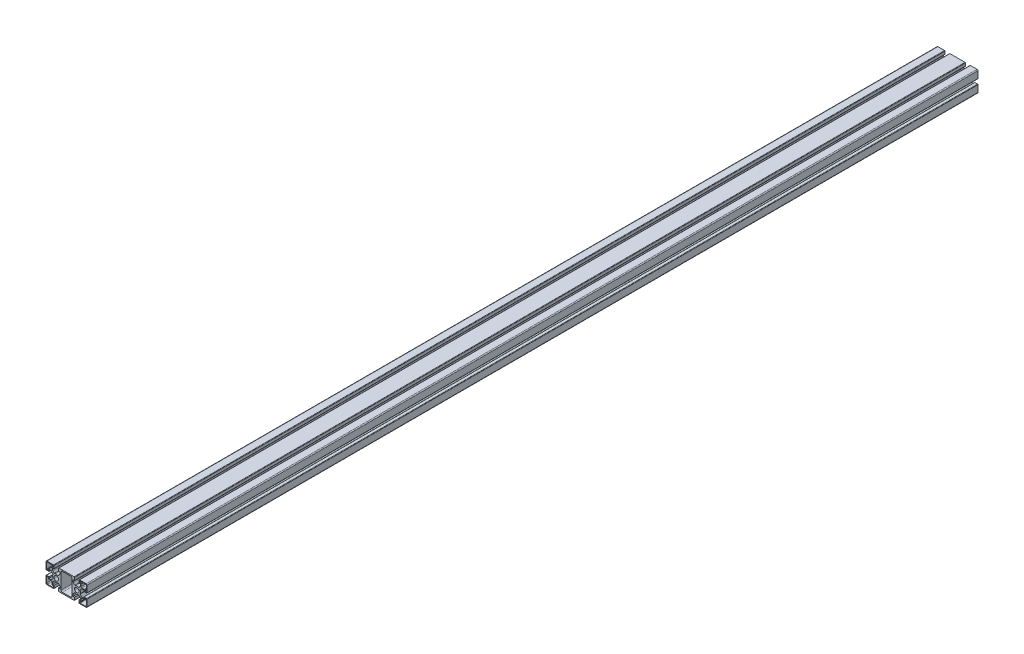
SolidWorks part; units mm, degrees
ref_plane "Front Plane" through (0, 0, 0) normal (0, 0, 1) x (1, 0, 0)
ref_plane "Top Plane" through (0, 0, 0) normal (0, 1, 0) x (1, 0, 0)
ref_plane "Right Plane" through (0, 0, 0) normal (1, 0, 0) x (0, 0, -1)
sketch "Sketch1" plane through (0, 0, 0) normal (0, 0, 1) x (1, 0, 0)
  line L0 (-5, -15.7059) -> (-8, -15.7059)
  line L1 (-20.5, -22.5) -> (-6, -22.5)
  line L2 (-22.5, -20.5) -> (-22.5, -6)
  line L5 (-21.9142, -21.9142) -> (22.5, 22.5) construction
  line L6 (-22.5, 22.5) -> (22.5, -22.5) construction
  line L7 (-20.5, -22.5) -> (-6, -22.5)
  line L8 (-22.5, -20.5) -> (-22.5, -6)
  line L10 (-5, -21.5) -> (-5, -15.7059)
  line L11 (-8, -15.7059) -> (-8, -11.9485)
  line L12 (-7.1213, -9.8272) -> (-4.6684, -7.3742)
  line L14 (-19, -21) -> (-7.5, -21)
  line L15 (-6.5, -20) -> (-6.5, -18.2059)
  line L16 (-7.5, -17.2059) -> (-8.5, -17.2059)
  line L17 (-9.5, -16.2059) -> (-9.5, -11.5)
  line L18 (-16.2059, -9.5) -> (-11.5, -9.5)
  line L19 (-17.2059, -7.5) -> (-17.2059, -8.5)
  line L20 (-20, -6.5) -> (-18.2059, -6.5)
  line L21 (-21, -19) -> (-21, -7.5)
  line L22 (-9.8272, -7.1213) -> (-7.3742, -4.6684)
  line L23 (-15.7059, -8) -> (-11.9485, -8)
  line L24 (-15.7059, -5) -> (-15.7059, -8)
  line L25 (-21.5, -5) -> (-15.7059, -5)
  line L26 (0, 27.7778) -> (0, -29.5537) construction
  line L28 (-9.5, 16.2059) -> (-9.5, 11.5)
  line L29 (-16.2059, 9.5) -> (-11.5, 9.5)
  line L30 (-17.2059, 7.5) -> (-17.2059, 8.5)
  line L31 (-20, 6.5) -> (-18.2059, 6.5)
  line L32 (-21, 19) -> (-21, 7.5)
  line L33 (-19, 21) -> (-7.5, 21)
  line L34 (-6.5, 20) -> (-6.5, 18.2059)
  line L35 (-7.5, 17.2059) -> (-8.5, 17.2059)
  line L36 (-22.5, 20.5) -> (-22.5, 6)
  line L37 (-20.5, 22.5) -> (-6, 22.5)
  line L38 (-5, 21.5) -> (-5, 15.7059)
  line L39 (-5, 15.7059) -> (-8, 15.7059)
  line L40 (-8, 15.7059) -> (-8, 11.9485)
  line L41 (-7.1213, 9.8272) -> (-4.6684, 7.3742)
  line L42 (-9.8272, 7.1213) -> (-7.3742, 4.6684)
  line L43 (-15.7059, 8) -> (-11.9485, 8)
  line L44 (-15.7059, 5) -> (-15.7059, 8)
  line L45 (-21.5, 5) -> (-15.7059, 5)
  line L54 (6, 22.5) -> (39, 22.5)
  line L56 (0, 0) -> (22.5, 0) construction
  line L57 (6, -22.5) -> (39, -22.5)
  line L58 (10.5, 17) -> (10.5, -17)
  line L59 (13.5, -20) -> (31.5, -20)
  line L60 (7.1213, 9.8272) -> (4.6684, 7.3742)
  line L61 (8, 15.7059) -> (8, 11.9485)
  line L62 (5, 15.7059) -> (8, 15.7059)
  line L63 (5, 21.5) -> (5, 15.7059)
  line L72 (13.5, 20) -> (31.5, 20)
  line L73 (22.5, 22.5) -> (22.5, -22.5) construction
  line L74 (5, -21.5) -> (5, -15.7059)
  line L75 (5, -15.7059) -> (8, -15.7059)
  line L76 (8, -15.7059) -> (8, -11.9485)
  line L77 (7.1213, -9.8272) -> (4.6684, -7.3742)
  line L78 (37.8787, -9.8272) -> (40.3316, -7.3742)
  line L79 (37, -15.7059) -> (37, -11.9485)
  line L80 (40, -15.7059) -> (37, -15.7059)
  line L81 (40, -21.5) -> (40, -15.7059)
  line L82 (21.5, 5) -> (15.7059, 5) [skipped]
  line L83 (20, 6.5) -> (18.2059, 6.5) [skipped]
  line L84 (21, 19) -> (21, 7.5) [skipped]
  line L85 (22.5, 20.5) -> (22.5, 6) [skipped]
  line L86 (15.7059, 5) -> (15.7059, 8) [skipped]
  line L87 (15.7059, 8) -> (11.9485, 8) [skipped]
  line L88 (16.2059, 9.5) -> (11.5, 9.5) [skipped]
  line L89 (17.2059, 7.5) -> (17.2059, 8.5) [skipped]
  line L90 (9.5, 16.2059) -> (9.5, 11.5) [skipped]
  line L91 (7.5, 17.2059) -> (8.5, 17.2059) [skipped]
  line L92 (6.5, 20) -> (6.5, 18.2059) [skipped]
  line L93 (19, 21) -> (7.5, 21) [skipped]
  line L94 (9.8272, 7.1213) -> (7.3742, 4.6684) [skipped]
  line L95 (6.5, -20) -> (6.5, -18.2059) [skipped]
  line L96 (19, -21) -> (7.5, -21) [skipped]
  line L97 (7.5, -17.2059) -> (8.5, -17.2059) [skipped]
  line L98 (9.5, -16.2059) -> (9.5, -11.5) [skipped]
  line L99 (22.5, -20.5) -> (22.5, -6) [skipped]
  line L100 (21, -19) -> (21, -7.5) [skipped]
  line L101 (20, -6.5) -> (18.2059, -6.5) [skipped]
  line L102 (21.5, -5) -> (15.7059, -5) [skipped]
  line L103 (17.2059, -7.5) -> (17.2059, -8.5) [skipped]
  line L104 (15.7059, -5) -> (15.7059, -8) [skipped]
  line L105 (9.8272, -7.1213) -> (7.3742, -4.6684) [skipped]
  line L106 (15.7059, -8) -> (11.9485, -8) [skipped]
  line L107 (16.2059, -9.5) -> (11.5, -9.5) [skipped]
  line L108 (20.5, 22.5) -> (6, 22.5) [skipped]
  line L109 (20.5, -22.5) -> (6, -22.5) [skipped]
  line L110 (40, 21.5) -> (40, 15.7059)
  line L111 (40, 15.7059) -> (37, 15.7059)
  line L112 (37, 15.7059) -> (37, 11.9485)
  line L113 (37.8787, 9.8272) -> (40.3316, 7.3742)
  line L114 (34.5, 17) -> (34.5, -17)
  line L115 (66.5, 5) -> (60.7059, 5)
  line L116 (60.7059, 5) -> (60.7059, 8)
  line L117 (60.7059, 8) -> (56.9485, 8)
  line L118 (54.8272, 7.1213) -> (52.3742, 4.6684)
  line L119 (52.1213, 9.8272) -> (49.6684, 7.3742)
  line L120 (53, 15.7059) -> (53, 11.9485)
  line L121 (50, 15.7059) -> (53, 15.7059)
  line L122 (50, 21.5) -> (50, 15.7059)
  line L123 (65.5, 22.5) -> (51, 22.5)
  line L124 (67.5, 20.5) -> (67.5, 6)
  line L125 (52.5, 17.2059) -> (53.5, 17.2059)
  line L126 (51.5, 20) -> (51.5, 18.2059)
  line L127 (64, 21) -> (52.5, 21)
  line L128 (66, 19) -> (66, 7.5)
  line L129 (65, 6.5) -> (63.2059, 6.5)
  line L130 (62.2059, 7.5) -> (62.2059, 8.5)
  line L131 (61.2059, 9.5) -> (56.5, 9.5)
  line L132 (54.5, 16.2059) -> (54.5, 11.5)
  line L133 (66.5, -5) -> (60.7059, -5)
  line L134 (60.7059, -5) -> (60.7059, -8)
  line L135 (60.7059, -8) -> (56.9485, -8)
  line L136 (54.8272, -7.1213) -> (52.3742, -4.6684)
  line L137 (66, -19) -> (66, -7.5)
  line L138 (65, -6.5) -> (63.2059, -6.5)
  line L139 (62.2059, -7.5) -> (62.2059, -8.5)
  line L140 (61.2059, -9.5) -> (56.5, -9.5)
  line L141 (54.5, -16.2059) -> (54.5, -11.5)
  line L142 (52.5, -17.2059) -> (53.5, -17.2059)
  line L143 (51.5, -20) -> (51.5, -18.2059)
  line L144 (64, -21) -> (52.5, -21)
  line L145 (52.1213, -9.8272) -> (49.6684, -7.3742)
  line L146 (53, -15.7059) -> (53, -11.9485)
  line L147 (50, -21.5) -> (50, -15.7059)
  line L148 (67.5, -20.5) -> (67.5, -6)
  line L149 (65.5, -22.5) -> (51, -22.5)
  line L150 (67.5, -20.5) -> (67.5, -6)
  line L151 (65.5, -22.5) -> (51, -22.5)
  line L152 (50, -15.7059) -> (53, -15.7059)
  circle A0 centre (0, 0) radius 5
  arc A1 (-3.5211, -7.1834) -> (3.5211, -7.1834) centre (0, 0) ccw
  arc A2 (-3.5211, -7.1834) -> (-4.6684, -7.3742) centre (-3.9613, -8.0814) ccw
  arc A3 (-8, -11.9485) -> (-7.1213, -9.8272) centre (-5, -11.9485) cw
  arc A4 (-6, -22.5) -> (-5, -21.5) centre (-6, -21.5) ccw
  arc A5 (-8.5, -17.2059) -> (-9.5, -16.2059) centre (-8.5, -16.2059) cw
  arc A6 (-6.5, -18.2059) -> (-7.5, -17.2059) centre (-7.5, -18.2059) ccw
  arc A7 (-6.5, -20) -> (-7.5, -21) centre (-7.5, -20) cw
  arc A8 (-17.2059, -8.5) -> (-16.2059, -9.5) centre (-16.2059, -8.5) ccw
  arc A9 (-18.2059, -6.5) -> (-17.2059, -7.5) centre (-18.2059, -7.5) cw
  arc A10 (-20, -6.5) -> (-21, -7.5) centre (-20, -7.5) ccw
  arc A11 (-22.5, -20.5) -> (-20.5, -22.5) centre (-20.5, -20.5) ccw
  arc A12 (-9.5, -11.5) -> (-11.5, -9.5) centre (-11.5, -11.5) ccw
  arc A13 (-19, -21) -> (-21, -19) centre (-19, -19) cw
  arc A14 (-7.1834, -3.5211) -> (-7.3742, -4.6684) centre (-8.0814, -3.9613) cw
  arc A15 (-11.9485, -8) -> (-9.8272, -7.1213) centre (-11.9485, -5) ccw
  arc A16 (-22.5, -6) -> (-21.5, -5) centre (-21.5, -6) cw
  arc A17 (-11.5, 9.5) -> (-9.5, 11.5) centre (-11.5, 11.5) ccw
  arc A18 (-17.2059, 8.5) -> (-16.2059, 9.5) centre (-16.2059, 8.5) cw
  arc A19 (-18.2059, 6.5) -> (-17.2059, 7.5) centre (-18.2059, 7.5) ccw
  arc A20 (-20, 6.5) -> (-21, 7.5) centre (-20, 7.5) cw
  arc A21 (-21, 19) -> (-19, 21) centre (-19, 19) cw
  arc A22 (-6.5, 20) -> (-7.5, 21) centre (-7.5, 20) ccw
  arc A23 (-6.5, 18.2059) -> (-7.5, 17.2059) centre (-7.5, 18.2059) cw
  arc A24 (-8.5, 17.2059) -> (-9.5, 16.2059) centre (-8.5, 16.2059) ccw
  arc A25 (-20.5, 22.5) -> (-22.5, 20.5) centre (-20.5, 20.5) ccw
  arc A26 (-6, 22.5) -> (-5, 21.5) centre (-6, 21.5) cw
  arc A27 (-8, 11.9485) -> (-7.1213, 9.8272) centre (-5, 11.9485) ccw
  arc A28 (-3.5211, 7.1834) -> (-4.6684, 7.3742) centre (-3.9613, 8.0814) cw
  arc A29 (-7.1834, 3.5211) -> (-7.3742, 4.6684) centre (-8.0814, 3.9613) ccw
  arc A30 (-11.9485, 8) -> (-9.8272, 7.1213) centre (-11.9485, 5) cw
  arc A31 (-22.5, 6) -> (-21.5, 5) centre (-21.5, 6) ccw
  arc A40 (10.5, -17) -> (13.5, -20) centre (13.5, -17) ccw
  arc A41 (13.5, 20) -> (10.5, 17) centre (13.5, 17) ccw
  arc A42 (41.4789, 7.1834) -> (48.5211, 7.1834) centre (45, 0) cw
  arc A43 (52.1834, 3.5211) -> (52.1834, -3.5211) centre (45, 0) cw
  arc A44 (3.5211, 7.1834) -> (4.6684, 7.3742) centre (3.9613, 8.0814) ccw
  arc A45 (8, 11.9485) -> (7.1213, 9.8272) centre (5, 11.9485) cw
  arc A46 (6, 22.5) -> (5, 21.5) centre (6, 21.5) ccw
  arc A55 (41.4789, -7.1834) -> (40.3316, -7.3742) centre (41.0387, -8.0814) ccw
  arc A56 (6, -22.5) -> (5, -21.5) centre (6, -21.5) cw
  arc A57 (8, -11.9485) -> (7.1213, -9.8272) centre (5, -11.9485) ccw
  arc A58 (3.5211, -7.1834) -> (4.6684, -7.3742) centre (3.9613, -8.0814) cw
  arc A59 (37, -11.9485) -> (37.8787, -9.8272) centre (40, -11.9485) cw
  arc A60 (39, -22.5) -> (40, -21.5) centre (39, -21.5) ccw
  arc A61 (39, 22.5) -> (40, 21.5) centre (39, 21.5) cw
  arc A62 (-7.1834, 3.5211) -> (-7.1834, -3.5211) centre (0, 0) ccw
  arc A63 (3.5211, 7.1834) -> (-3.5211, 7.1834) centre (0, 0) ccw
  arc A64 (37, 11.9485) -> (37.8787, 9.8272) centre (40, 11.9485) ccw
  arc A65 (22.5, 6) -> (21.5, 5) centre (21.5, 6) cw [skipped]
  arc A66 (20, 6.5) -> (21, 7.5) centre (20, 7.5) ccw [skipped]
  arc A67 (18.2059, 6.5) -> (17.2059, 7.5) centre (18.2059, 7.5) cw [skipped]
  arc A68 (17.2059, 8.5) -> (16.2059, 9.5) centre (16.2059, 8.5) ccw [skipped]
  arc A69 (8.5, 17.2059) -> (9.5, 16.2059) centre (8.5, 16.2059) cw [skipped]
  arc A70 (6.5, 18.2059) -> (7.5, 17.2059) centre (7.5, 18.2059) ccw [skipped]
  arc A71 (6.5, 20) -> (7.5, 21) centre (7.5, 20) cw [skipped]
  arc A72 (19, 21) -> (20.4142, 20.4142) centre (19, 19) cw [skipped]
  arc A73 (9.5, 11.5) -> (10.0858, 10.0858) centre (11.5, 11.5) ccw [skipped]
  arc A74 (7.1834, 3.5211) -> (7.3742, 4.6684) centre (8.0814, 3.9613) cw [skipped]
  arc A75 (11.9485, 8) -> (9.8272, 7.1213) centre (11.9485, 5) ccw [skipped]
  arc A76 (6.5, -20) -> (7.5, -21) centre (7.5, -20) ccw [skipped]
  arc A77 (8.5, -17.2059) -> (9.5, -16.2059) centre (8.5, -16.2059) ccw [skipped]
  arc A78 (6.5, -18.2059) -> (7.5, -17.2059) centre (7.5, -18.2059) cw [skipped]
  arc A79 (21, -19) -> (20.4142, -20.4142) centre (19, -19) cw [skipped]
  arc A80 (22.5, -6) -> (21.5, -5) centre (21.5, -6) ccw [skipped]
  arc A81 (20, -6.5) -> (21, -7.5) centre (20, -7.5) cw [skipped]
  arc A82 (17.2059, -8.5) -> (16.2059, -9.5) centre (16.2059, -8.5) cw [skipped]
  arc A83 (18.2059, -6.5) -> (17.2059, -7.5) centre (18.2059, -7.5) ccw [skipped]
  arc A84 (7.1834, -3.5211) -> (7.3742, -4.6684) centre (8.0814, -3.9613) ccw [skipped]
  arc A85 (11.9485, -8) -> (9.8272, -7.1213) centre (11.9485, -5) cw [skipped]
  arc A86 (11.5, -9.5) -> (10.0858, -10.0858) centre (11.5, -11.5) ccw [skipped]
  arc A87 (21.9142, 21.9142) -> (20.5, 22.5) centre (20.5, 20.5) ccw [skipped]
  arc A88 (20.5, -22.5) -> (21.9142, -21.9142) centre (20.5, -20.5) ccw [skipped]
  arc A89 (41.4789, 7.1834) -> (40.3316, 7.3742) centre (41.0387, 8.0814) cw
  arc A90 (31.5, 20) -> (34.5, 17) centre (31.5, 17) cw
  arc A91 (34.5, -17) -> (31.5, -20) centre (31.5, -17) cw
  arc A92 (67.5, 6) -> (66.5, 5) centre (66.5, 6) cw
  arc A93 (56.9485, 8) -> (54.8272, 7.1213) centre (56.9485, 5) ccw
  arc A94 (52.1834, 3.5211) -> (52.3742, 4.6684) centre (53.0814, 3.9613) cw
  arc A95 (48.5211, 7.1834) -> (49.6684, 7.3742) centre (48.9613, 8.0814) ccw
  arc A96 (53, 11.9485) -> (52.1213, 9.8272) centre (50, 11.9485) cw
  arc A97 (51, 22.5) -> (50, 21.5) centre (51, 21.5) ccw
  arc A98 (65.5, 22.5) -> (67.5, 20.5) centre (65.5, 20.5) cw
  arc A99 (53.5, 17.2059) -> (54.5, 16.2059) centre (53.5, 16.2059) cw
  arc A100 (51.5, 18.2059) -> (52.5, 17.2059) centre (52.5, 18.2059) ccw
  arc A101 (51.5, 20) -> (52.5, 21) centre (52.5, 20) cw
  arc A102 (66, 19) -> (64, 21) centre (64, 19) ccw
  arc A103 (65, 6.5) -> (66, 7.5) centre (65, 7.5) ccw
  arc A104 (63.2059, 6.5) -> (62.2059, 7.5) centre (63.2059, 7.5) cw
  arc A105 (62.2059, 8.5) -> (61.2059, 9.5) centre (61.2059, 8.5) ccw
  arc A106 (56.5, 9.5) -> (54.5, 11.5) centre (56.5, 11.5) cw
  arc A107 (67.5, -6) -> (66.5, -5) centre (66.5, -6) ccw
  arc A108 (56.9485, -8) -> (54.8272, -7.1213) centre (56.9485, -5) cw
  arc A109 (52.1834, -3.5211) -> (52.3742, -4.6684) centre (53.0814, -3.9613) ccw
  arc A110 (64, -21) -> (66, -19) centre (64, -19) ccw
  arc A111 (54.5, -11.5) -> (56.5, -9.5) centre (56.5, -11.5) cw
  arc A112 (67.5, -20.5) -> (65.5, -22.5) centre (65.5, -20.5) cw
  arc A113 (65, -6.5) -> (66, -7.5) centre (65, -7.5) cw
  arc A114 (63.2059, -6.5) -> (62.2059, -7.5) centre (63.2059, -7.5) ccw
  arc A115 (62.2059, -8.5) -> (61.2059, -9.5) centre (61.2059, -8.5) cw
  arc A116 (51.5, -20) -> (52.5, -21) centre (52.5, -20) ccw
  arc A117 (51.5, -18.2059) -> (52.5, -17.2059) centre (52.5, -18.2059) cw
  arc A118 (53.5, -17.2059) -> (54.5, -16.2059) centre (53.5, -16.2059) ccw
  arc A119 (51, -22.5) -> (50, -21.5) centre (51, -21.5) cw
  arc A120 (53, -11.9485) -> (52.1213, -9.8272) centre (50, -11.9485) ccw
  arc A121 (48.5211, -7.1834) -> (49.6684, -7.3742) centre (48.9613, -8.0814) cw
  arc A122 (48.5211, -7.1834) -> (41.4789, -7.1834) centre (45, 0) cw
  circle A123 centre (45, 0) radius 5
  point P0 (0, 0)
  point P19 (-8, -10.7059)
  point P48 (-9.5, -9.5)
  point P51 (-21, -21)
  point P65 (8, 13.8272)
  point P214 (0, 0)
  point P390 (22.5, 20)
  point P392 (22.5, -20)
  point P400 (45, 0)
  point P401 (66, -21)
  point P402 (54.5, -9.5)
  point P403 (53, -10.7059)
  point P404 (45, 0)
  dimension "D3" = 17.5
  dimension "D5" = 1
  dimension "D6" = 3
  dimension "D2" = 1
  dimension "D11" = 1
  dimension "D12" = 2
  dimension "D18" = 3
  dimension "D1" = 45
  dimension "D4" = 5
  dimension "D7" = 1.5
  dimension "D8" = 1.5
  dimension "D9" = 1.5
  dimension "D10" = 1.5
  dimension "D14" = 22.5
  dimension "D15" = 2.5
  dimension "D16" = 2.5
  dimension "D17" = 2.5
  dimension "D13" = 4
extrude "Boss-Extrude2" add sketch "Sketch1" along normal blind 1955 contours A122 A121 L145 A120 L146 L152 L147 A119 L149 A112 L148 A107 L133 L134 L135 A108 L136 A109 A43 A94 L118 A93 L117 L116 L115 A92 L124 A98 L123 A97 L122 L121 L120 A96 L119 A95 A42 A89 L113 A64 L112 L111 L110 A61 L54 A46 L63 L62 L61 A45 L60
sketch "Sketch2" plane through (0, 0, 0) normal (0, 1, 0) x (1, 0, 0)
  line L0 (45, -1955) -> (45, 131.2627) construction
  line L1 (41.4789, -1955) -> (48.5211, -1955) construction
  line L2 (0, -1955) -> (0, 104.0594) construction
  line L3 (-3.5211, -1955) -> (3.5211, -1955) construction
